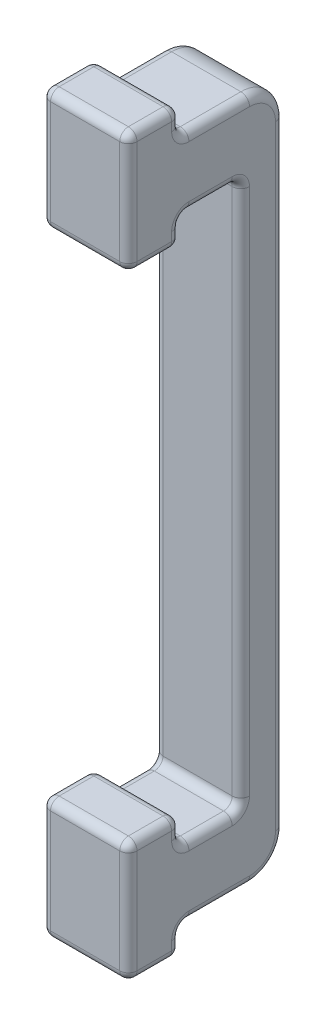
SolidWorks part; units mm, degrees
ref_plane "Front Plane" through (0, 0, 0) normal (0, 0, 1) x (1, 0, 0)
ref_plane "Top Plane" through (0, 0, 0) normal (0, 1, 0) x (1, 0, 0)
ref_plane "Right Plane" through (0, 0, 0) normal (1, 0, 0) x (0, 0, -1)
sketch "Sketch1" plane through (0, 0, 0) normal (1, 0, 0) x (0, 0, -1)
  line L0 (1, 0) -> (5, 0)
  line L1 (6, 1) -> (6, 2)
  line L2 (7, 3) -> (13, 3)
  line L3 (13, 3) -> (13, 11) construction
  line L4 (12, 11) -> (7, 11)
  line L5 (6, 12) -> (6, 13)
  line L6 (5, 14) -> (1, 14)
  line L7 (0, 13) -> (0, 1)
  line L8 (0, 84) -> (0, 72)
  line L9 (1, 71) -> (5, 71)
  line L10 (6, 72) -> (6, 73)
  line L11 (7, 74) -> (12, 74)
  line L12 (13, 74) -> (13, 82) construction
  line L13 (13, 82) -> (7, 82)
  line L14 (6, 83) -> (6, 84)
  line L15 (5, 85) -> (1, 85)
  line L16 (13, 73) -> (13, 12)
  line L17 (13, 3) -> (14, 3)
  line L18 (18, 7) -> (18, 78)
  line L19 (14, 82) -> (13, 82)
  arc A0 (13, 12) -> (12, 11) centre (12, 12) cw
  arc A1 (7, 11) -> (6, 12) centre (7, 12) cw
  arc A2 (6, 2) -> (7, 3) centre (7, 2) cw
  arc A3 (5, 0) -> (6, 1) centre (5, 1) ccw
  arc A4 (1, 0) -> (0, 1) centre (1, 1) cw
  arc A5 (1, 14) -> (0, 13) centre (1, 13) ccw
  arc A6 (6, 13) -> (5, 14) centre (5, 13) ccw
  arc A7 (12, 74) -> (13, 73) centre (12, 73) cw
  arc A8 (0, 72) -> (1, 71) centre (1, 72) ccw
  arc A9 (5, 71) -> (6, 72) centre (5, 72) ccw
  arc A10 (6, 73) -> (7, 74) centre (7, 73) cw
  arc A11 (7, 82) -> (6, 83) centre (7, 83) cw
  arc A12 (6, 84) -> (5, 85) centre (5, 84) ccw
  arc A13 (0, 84) -> (1, 85) centre (1, 84) cw
  arc A14 (14, 3) -> (18, 7) centre (14, 7) ccw
  arc A15 (18, 78) -> (14, 82) centre (14, 78) ccw
  point P25 (6, 11)
  point P28 (6, 3)
  point P33 (0, 0)
  point P36 (0, 14)
  point P39 (6, 14)
  point P59 (18, 82)
  dimension "D8" = 1
  dimension "D9" = 4
  dimension "D1" = 14
  dimension "D2" = 6
  dimension "D3" = 3
  dimension "D4" = 7
  dimension "D6" = 71
  dimension "D7" = 5
  dimension "D5" = 2
extrude "Boss-Extrude1" add sketch "Sketch1" along normal blind 10
fillet "Fillet1" radius 1 64 edges at (10, 73.7071, -12.7071) (10, 74, -9.5) (10, 73.7071, -6.2929) (10, 72.5, -6) (10, 71.2929, -5.7071) (10, 71, -3) (10, 71.2929, -0.2929) (10, 78, 0) (10, 84.7071, -0.2929) (10, 85, -3) (10, 84.7071, -5.7071) (10, 83.5, -6) (10, 82.2929, -6.2929) (10, 82, -10.5) (10, 80.8284, -16.8284) (10, 42.5, -18) (10, 4.1716, -16.8284) (10, 3, -10.5) (10, 2.7071, -6.2929) (10, 1.5, -6) (10, 0.2929, -5.7071) (10, 0, -3) (10, 0.2929, -0.2929) (10, 7, 0) (10, 13.7071, -0.2929) (10, 14, -3) (10, 13.7071, -5.7071) (10, 12.5, -6) (10, 11.2929, -6.2929) (10, 11, -9.5) (10, 11.2929, -12.7071) (0, 73.7071, -12.7071) (0, 74, -9.5) (0, 73.7071, -6.2929) (0, 72.5, -6) (0, 71.2929, -5.7071) (0, 71, -3) (0, 71.2929, -0.2929) (0, 78, 0) (0, 84.7071, -0.2929) (0, 85, -3) (0, 84.7071, -5.7071) (0, 83.5, -6) (0, 82.2929, -6.2929) (0, 82, -10.5) (0, 80.8284, -16.8284) (0, 42.5, -18) (0, 4.1716, -16.8284) (0, 3, -10.5) (0, 2.7071, -6.2929) (0, 1.5, -6) (0, 0.2929, -5.7071) (0, 0, -3) (0, 0.2929, -0.2929) (0, 7, 0) (0, 13.7071, -0.2929) (0, 14, -3) (0, 13.7071, -5.7071) (0, 12.5, -6) (0, 11.2929, -6.2929) (0, 11, -9.5) (0, 11.2929, -12.7071) (10, 42.5, -13) (0, 42.5, -13)
